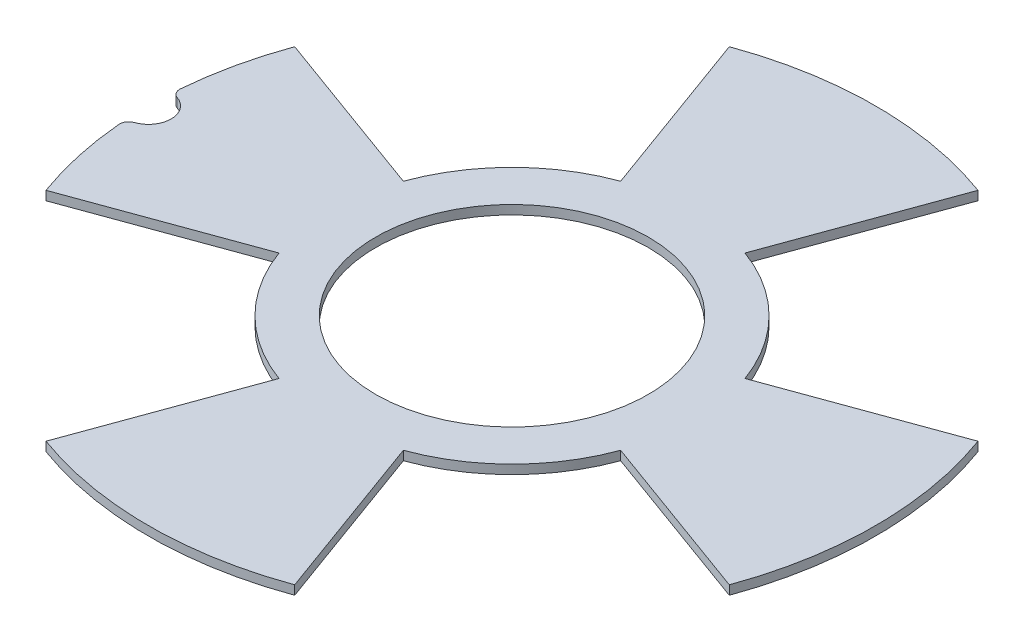
SolidWorks part; units mm, degrees
ref_plane "Front Plane" through (0, 0, 0) normal (0, 0, 1) x (1, 0, 0)
ref_plane "Top Plane" through (0, 0, 0) normal (0, 1, 0) x (1, 0, 0)
ref_plane "Right Plane" through (0, 0, 0) normal (1, 0, 0) x (0, 0, -1)
sketch "Sketch1" plane through (0, 0, 0) normal (0, 1, 0) x (1, 0, 0)
  line L2 (37.5877, -13.6808) -> (18.7939, -6.8404)
  line L3 (-13.6808, -37.5877) -> (-6.8404, -18.7939)
  line L4 (13.6808, -37.5877) -> (6.8404, -18.7939)
  line L5 (37.5877, 13.6808) -> (18.7939, 6.8404)
  line L6 (-6.8404, 18.7939) -> (-13.6808, 37.5877)
  line L8 (6.8404, 18.7939) -> (13.6808, 37.5877)
  line L9 (-18.7939, -6.8404) -> (-37.5877, -13.6808)
  line L11 (-18.7939, 6.8404) -> (-37.5877, 13.6808)
  arc A0 (-39.8558, -3.3938) -> (-37.5877, -13.6808) centre (0, 0) ccw
  circle A1 centre (0, 0) radius 15
  arc A2 (-39.1853, -2.3635) -> (-39.1853, 2.3635) centre (-40, 0) ccw
  arc A3 (-39.1853, 2.3635) -> (-39.8558, 3.3938) centre (-38.8594, 3.3089) cw
  arc A4 (-39.8558, -3.3938) -> (-39.1853, -2.3635) centre (-38.8594, -3.3089) cw
  arc A5 (13.6808, 37.5877) -> (-13.6808, 37.5877) centre (0, 0) ccw
  arc A6 (-37.5877, 13.6808) -> (-39.8558, 3.3938) centre (0, 0) ccw
  arc A7 (37.5877, -13.6808) -> (37.5877, 13.6808) centre (0, 0) ccw
  arc A8 (-13.6808, -37.5877) -> (13.6808, -37.5877) centre (0, 0) ccw
  arc A9 (18.7939, 6.8404) -> (6.8404, 18.7939) centre (0, 0) ccw
  arc A10 (6.8404, -18.7939) -> (18.7939, -6.8404) centre (0, 0) ccw
  arc A11 (-18.7939, -6.8404) -> (-6.8404, -18.7939) centre (0, 0) ccw
  arc A17 (-6.8404, 18.7939) -> (-18.7939, 6.8404) centre (0, 0) ccw
  dimension "D1" = 80
  dimension "D2" = 30
  dimension "D3" = 5
  dimension "D4" = 1
  dimension "D5" = 1
  dimension "D8" = 40
extrude "Boss-Extrude1" add sketch "Sketch1" along normal blind 1
